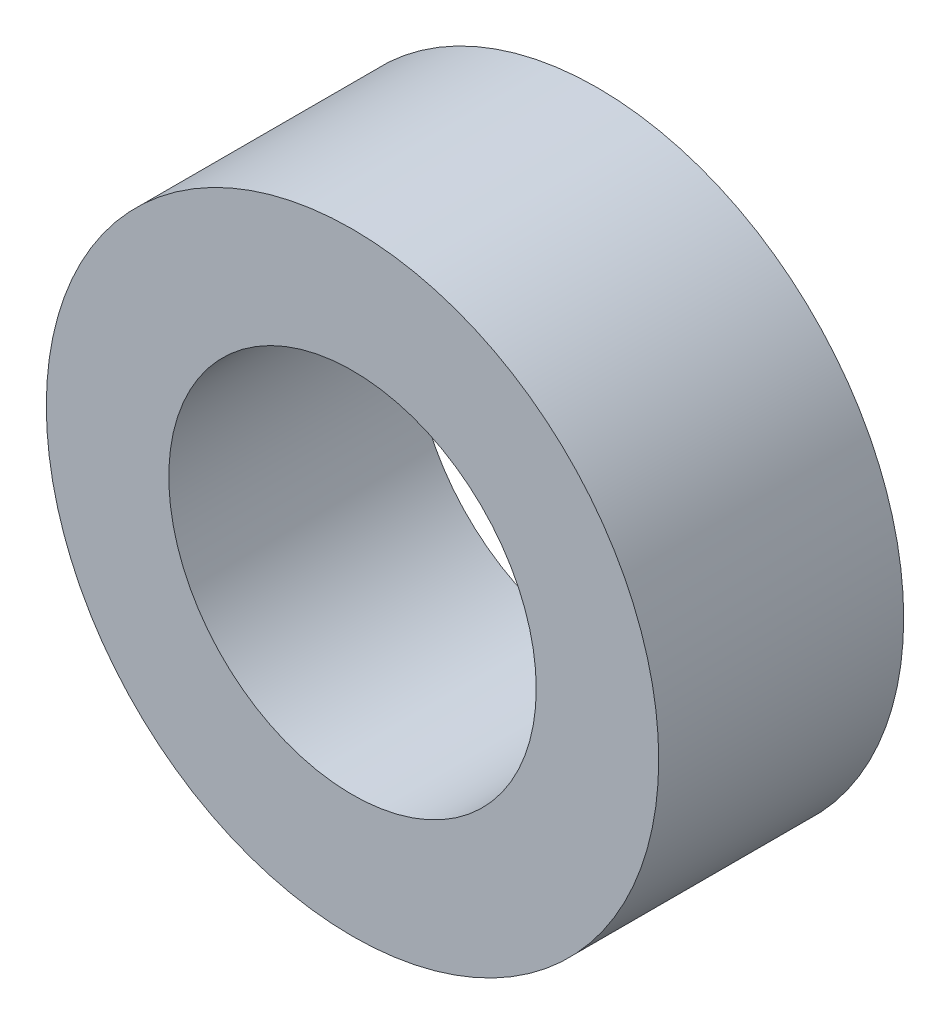
SolidWorks part; units mm, degrees
ref_plane "정면" through (0, 0, 0) normal (0, 0, 1) x (1, 0, 0)
ref_plane "윗면" through (0, 0, 0) normal (0, 1, 0) x (1, 0, 0)
ref_plane "우측면" through (0, 0, 0) normal (1, 0, 0) x (0, 0, -1)
sketch "스케치1" plane through (0, 0, 0) normal (0, 0, 1) x (1, 0, 0)
  circle A0 centre (0, 0) radius 7.5
  circle A1 centre (0, 0) radius 12.5
  dimension "D1" = 15
  dimension "D2" = 5
extrude "보스-돌출1" add sketch "스케치1" along normal blind 10
